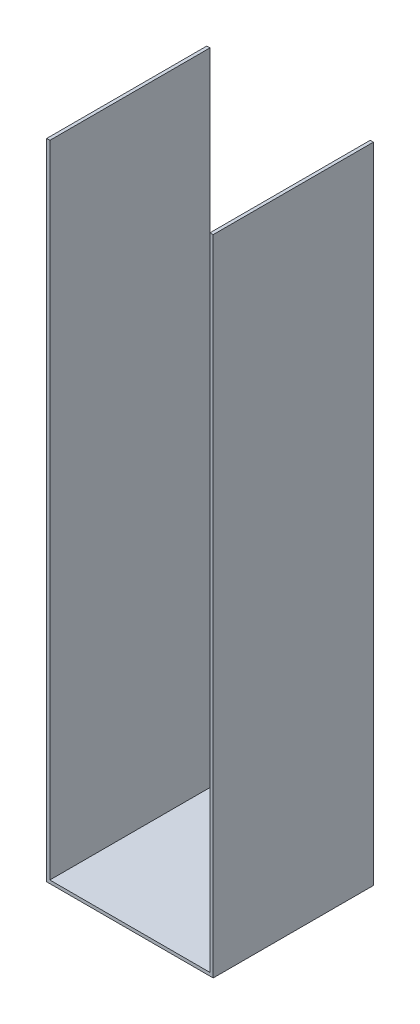
SolidWorks part; units mm, degrees
ref_plane "Front Plane" through (0, 0, 0) normal (0, 0, 1) x (1, 0, 0)
ref_plane "Top Plane" through (0, 0, 0) normal (0, 1, 0) x (1, 0, 0)
ref_plane "Right Plane" through (0, 0, 0) normal (1, 0, 0) x (0, 0, -1)
sketch "Sketch1" plane through (0, 0, 0) normal (0, 0, 1) x (1, 0, 0)
  line L0 (0, 0) -> (0, -40000)
  line L1 (0, -40000) -> (10000, -40000)
  line L2 (10000, -40000) -> (10000, 0)
  line L3 (-200, 0) -> (-200, -40200)
  line L4 (-200, -40200) -> (10200, -40200)
  line L5 (10200, -40200) -> (10200, 0)
  line L6 (-200, 0) -> (0, 0)
  line L7 (10000, 0) -> (10200, 0)
extrude "Boss-Extrude1" add sketch "Sketch1" along normal blind 10000
